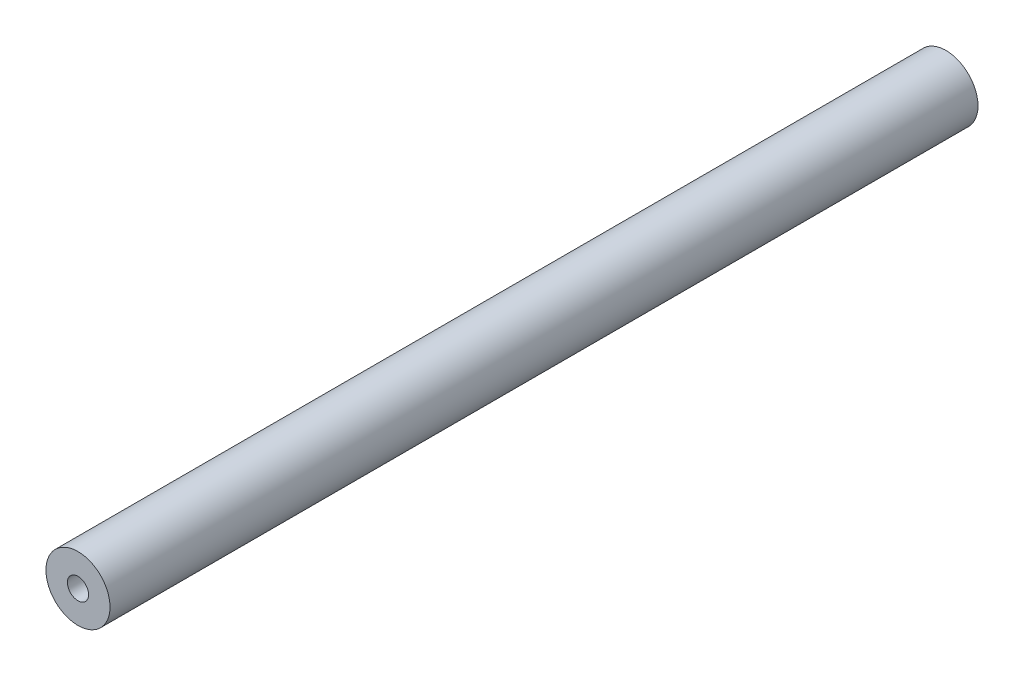
SolidWorks part; units mm, degrees
material "5052-H34"
ref_plane "正面" through (0, 0, 0) normal (0, 0, 1) x (1, 0, 0)
ref_plane "平面" through (0, 0, 0) normal (0, 1, 0) x (1, 0, 0)
ref_plane "右側面" through (0, 0, 0) normal (1, 0, 0) x (0, 0, -1)
sketch "ｽｹｯﾁ1" plane through (0, 0, 0) normal (0, 0, 1) x (1, 0, 0)
  circle A0 centre (0, 0) radius 5
  dimension "D1" = 10
extrude "ﾎﾞｽ - 押し出し1" add sketch "ｽｹｯﾁ1" along normal blind 135.5
sketch "ｽｹｯﾁ2" plane through (0, 0, 135.5) normal (0, 0, 1) x (1, 0, 0)
  circle A0 centre (0, 0) radius 1.65
  dimension "D1" = 3.3
extrude "ｶｯﾄ - 押し出し1" cut sketch "ｽｹｯﾁ2" against normal blind 10
sketch "ｽｹｯﾁ3" plane through (0, 0, 0) normal (0, 0, -1) x (-1, 0, 0)
  circle A0 centre (0, 0) radius 1.65
  dimension "D1" = 3.3
extrude "ｶｯﾄ - 押し出し2" cut sketch "ｽｹｯﾁ3" against normal blind 10
